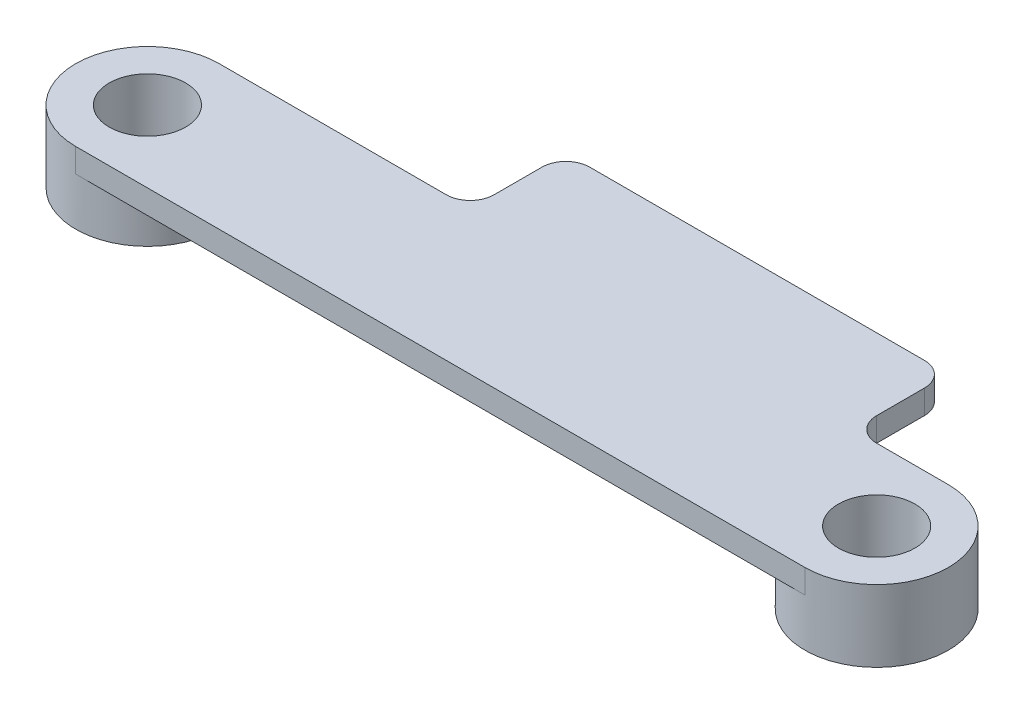
SolidWorks part; units mm, degrees
ref_plane "Front Plane" through (0, 0, 0) normal (0, 0, 1) x (1, 0, 0)
ref_plane "Top Plane" through (0, 0, 0) normal (0, 1, 0) x (1, 0, 0)
ref_plane "Right Plane" through (0, 0, 0) normal (1, 0, 0) x (0, 0, -1)
sketch "Sketch1" plane through (0, 0, 0) normal (0, 1, 0) x (1, 0, 0)
  line L0 (-15.25, 0) -> (15.25, 0) construction
  line L1 (-15.25, 0) -> (15.25, 0) construction
  line L2 (-15.25, 3) -> (15.25, 3)
  line L3 (-15.25, -3) -> (15.25, -3)
  line L5 (-4.75, -3) -> (11.25, -3)
  line L6 (-4.75, -3) -> (-4.75, 7)
  line L7 (-4.75, 7) -> (11.25, 7)
  line L8 (11.25, -3) -> (11.25, 7)
  circle A0 centre (-15.25, 0) radius 1.6
  circle A1 centre (15.25, 0) radius 1.6
  arc A2 (-15.25, 3) -> (-15.25, -3) centre (-15.25, 0) ccw
  arc A3 (15.25, -3) -> (15.25, 3) centre (15.25, 0) ccw
  point P5 (0, 0)
  dimension "D2" = 3.2
  dimension "D3" = 3.2
  dimension "D4" = 3
  dimension "D1" = 30.5
  dimension "D5" = 16
  dimension "D6" = 10
  dimension "D7" = 4
extrude "Boss-Extrude1" add sketch "Sketch1" along normal blind 1 contours L3 L8 L2 L6 | L2 L8 L7 L6 | L2 A2 L3 L6 A0 | L3 A3 L2 L8 A1
fillet "Fillet1" radius 1 4 edges at (11.25, 0.5, -3) (11.25, 0.5, -7) (-4.75, 0.5, -7) (-4.75, 0.5, -3)
sketch "Sketch2" plane through (0, 0, 0) normal (0, -1, 0) x (1, 0, 0)
  circle A0 centre (-15.25, 0) radius 1.6
  circle A1 centre (-15.25, 0) radius 3
  circle A2 centre (15.25, 0) radius 3
  circle A3 centre (15.25, 0) radius 1.6
extrude "Boss-Extrude2" add sketch "Sketch2" along normal blind 2
